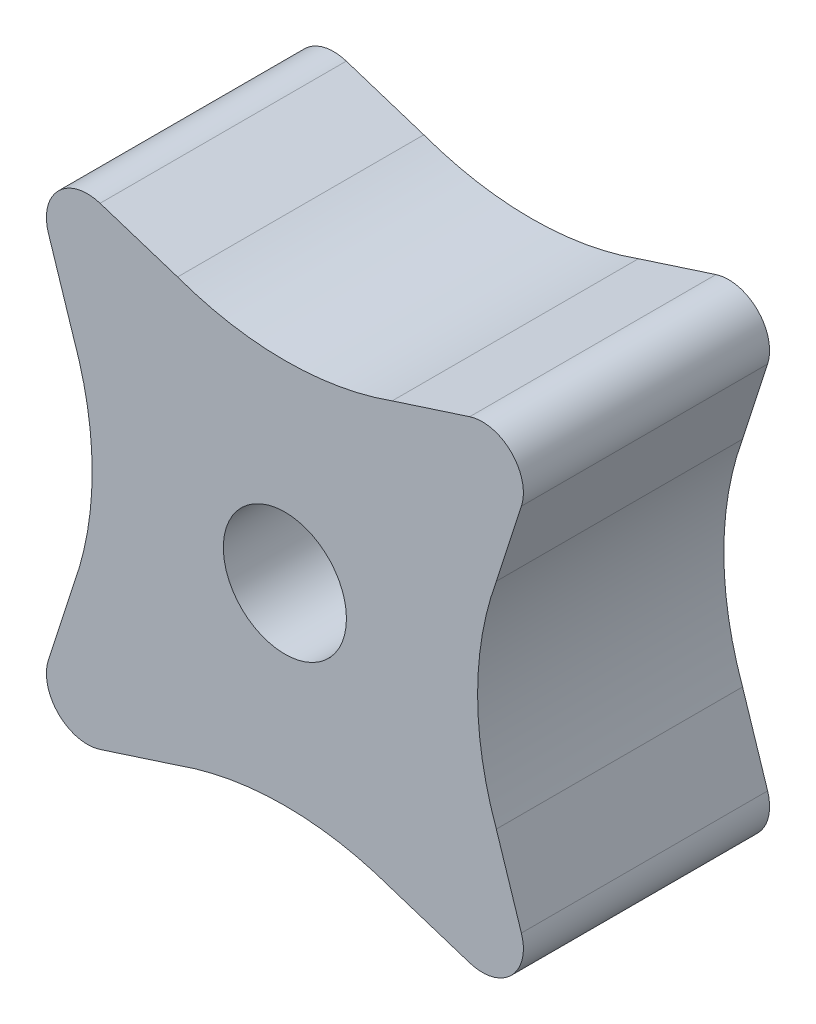
SolidWorks part; units mm, degrees
ref_plane "Alzado" through (0, 0, 0) normal (0, 0, 1) x (1, 0, 0)
ref_plane "Planta" through (0, 0, 0) normal (0, 1, 0) x (1, 0, 0)
ref_plane "Vista lateral" through (0, 0, 0) normal (1, 0, 0) x (0, 0, -1)
sketch "Croquis1" plane through (0, 0, 0) normal (0, 0, 1) x (1, 0, 0)
  line L0 (0, 0) -> (27.8544, 27.8544) construction
  line L1 (0, 0) -> (-42.4264, 42.4264) construction
  line L2 (0, 0) -> (0, 42.4264) construction
  line L3 (15.25, -15.25) -> (-15.25, -15.25) construction
  line L4 (15.25, -15.25) -> (15.25, 15.25) construction
  line L5 (15.25, 15.25) -> (-15.25, 15.25) construction
  line L6 (-15.25, -15.25) -> (-15.25, 15.25) construction
  line L7 (15.25, -15.25) -> (-15.25, 15.25) construction
  line L8 (15.25, 15.25) -> (-15.25, -15.25) construction
  line L9 (0, 42.4264) -> (-20, 42.4264) construction
  line L10 (-42.4264, 42.4264) -> (-38.8909, 45.9619) construction
  line L11 (-38.8909, 45.9619) -> (-31.0962, 38.1673) construction
  line L12 (-20, 42.7635) -> (-20, 80) construction
  line L13 (-42.4264, 42.4264) -> (-45.9619, 38.8909) construction
  line L14 (-45.9619, 38.8909) -> (-38.1673, 31.0962) construction
  line L15 (20, 42.7635) -> (20, 80) construction
  line L16 (38.8909, 45.9619) -> (31.0962, 38.1673) construction
  line L17 (42.4264, 42.4264) -> (38.8909, 45.9619) construction
  line L18 (42.4264, 42.4264) -> (45.9619, 38.8909) construction
  line L19 (-45.9619, -38.8909) -> (-38.1673, -31.0962) construction
  line L20 (0, 0) -> (-15.25, 0) construction
  line L21 (45.9619, 38.8909) -> (38.1673, 31.0962) construction
  line L22 (42.4264, -42.4264) -> (45.9619, -38.8909) construction
  line L23 (42.4264, -42.4264) -> (38.8909, -45.9619) construction
  line L24 (38.8909, -45.9619) -> (31.0962, -38.1673) construction
  line L25 (20, -42.7635) -> (20, -80) construction
  line L26 (-20, -42.7635) -> (-20, -80) construction
  line L27 (-38.8909, -45.9619) -> (-31.0962, -38.1673) construction
  line L28 (-42.4264, -42.4264) -> (-38.8909, -45.9619) construction
  line L29 (-42.4264, -42.4264) -> (-45.9619, -38.8909) construction
  line L30 (45.9619, -38.8909) -> (38.1673, -31.0962) construction
  line L31 (-20, 80) -> (20, 80) construction
  line L32 (0, 80) -> (0, 83) construction
  line L33 (-20, 80) -> (0, 83) construction
  line L34 (0, 83) -> (20, 80) construction
  line L35 (0, -80) -> (0, -83) construction
  line L36 (-20, -80) -> (20, -80) construction
  line L37 (0, -83) -> (20, -80) construction
  line L38 (-20, -80) -> (0, -83) construction
  line L39 (-11, -54) -> (-11, -67.5) construction
  line L41 (-15, -54) -> (-15, -67.5) construction
  line L43 (-13, -54) -> (-13, -67.5) construction
  line L44 (-9, -54) -> (-9, -67.5) construction
  line L45 (-7, -54) -> (-7, -67.5) construction
  line L46 (-5, -54) -> (-5, -67.5) construction
  line L47 (-3, -54) -> (-3, -67.5) construction
  line L48 (-1, -54) -> (-1, -67.5) construction
  line L49 (1, -54) -> (1, -67.5) construction
  line L50 (3, -54) -> (3, -67.5) construction
  line L51 (5, -54) -> (5, -67.5) construction
  line L52 (7, -54) -> (7, -67.5) construction
  line L53 (9, -54) -> (9, -67.5) construction
  line L54 (11, -54) -> (11, -67.5) construction
  line L55 (13, -54) -> (13, -67.5) construction
  line L56 (15, -54) -> (15, -67.5) construction
  line L57 (-11, -35) -> (-11, -48.5) construction
  line L58 (-9, -35) -> (-9, -48.5) construction
  line L59 (-7, -35) -> (-7, -48.5) construction
  line L60 (-5, -35) -> (-5, -48.5) construction
  line L61 (-3, -35) -> (-3, -48.5) construction
  line L62 (-1, -35) -> (-1, -48.5) construction
  line L63 (1, -35) -> (1, -48.5) construction
  line L64 (3, -35) -> (3, -48.5) construction
  line L65 (5, -35) -> (5, -48.5) construction
  line L66 (7, -35) -> (7, -48.5) construction
  line L67 (9, -35) -> (9, -48.5) construction
  line L68 (11, -35) -> (11, -48.5) construction
  line L69 (13, -35) -> (13, -48.5) construction
  line L70 (15, -35) -> (15, -48.5) construction
  line L71 (-15, -35) -> (-15, -48.5) construction
  line L72 (-13, -35) -> (-13, -48.5) construction
  line L73 (-15, 54) -> (-15, 67.5) construction
  line L74 (-13, 35) -> (-13, 48.5) construction
  line L75 (-15, 35) -> (-15, 48.5) construction
  line L76 (15, 35) -> (15, 48.5) construction
  line L77 (13, 35) -> (13, 48.5) construction
  line L78 (11, 35) -> (11, 48.5) construction
  line L79 (9, 35) -> (9, 48.5) construction
  line L80 (7, 35) -> (7, 48.5) construction
  line L81 (5, 35) -> (5, 48.5) construction
  line L82 (3, 35) -> (3, 48.5) construction
  line L83 (1, 35) -> (1, 48.5) construction
  line L84 (-1, 35) -> (-1, 48.5) construction
  line L85 (-3, 35) -> (-3, 48.5) construction
  line L86 (-5, 35) -> (-5, 48.5) construction
  line L87 (-7, 35) -> (-7, 48.5) construction
  line L88 (-9, 35) -> (-9, 48.5) construction
  line L89 (-11, 35) -> (-11, 48.5) construction
  line L90 (15, 54) -> (15, 67.5) construction
  line L91 (13, 54) -> (13, 67.5) construction
  line L92 (11, 54) -> (11, 67.5) construction
  line L93 (9, 54) -> (9, 67.5) construction
  line L94 (7, 54) -> (7, 67.5) construction
  line L95 (5, 54) -> (5, 67.5) construction
  line L96 (3, 54) -> (3, 67.5) construction
  line L97 (1, 54) -> (1, 67.5) construction
  line L98 (-1, 54) -> (-1, 67.5) construction
  line L99 (-3, 54) -> (-3, 67.5) construction
  line L100 (-5, 54) -> (-5, 67.5) construction
  line L101 (-7, 54) -> (-7, 67.5) construction
  line L102 (-9, 54) -> (-9, 67.5) construction
  line L103 (-13, 54) -> (-13, 67.5) construction
  line L104 (-11, 54) -> (-11, 67.5) construction
  line L105 (0, 0) -> (-8.4853, -8.4853) construction
  line L110 (-5.7118, -4.325) -> (-4.3076, -2.2188) construction
  line L111 (-4.325, -5.7118) -> (-2.2188, -4.3076) construction
  line L112 (-4.325, 5.7118) -> (-2.2188, 4.3076) construction
  line L113 (-5.7118, 4.325) -> (-4.3076, 2.2188) construction
  line L114 (5.7118, 4.325) -> (4.3076, 2.2188) construction
  line L115 (4.325, 5.7118) -> (2.2188, 4.3076) construction
  line L116 (4.325, -5.7118) -> (2.2188, -4.3076) construction
  line L117 (5.7118, -4.325) -> (4.3076, -2.2188) construction
  line L118 (0, 0) -> (-84.8528, 84.8528) construction
  line L123 (-45.9619, 38.8909) -> (-31.0962, 24.0251) construction
  line L124 (-17.1122, 2.2943) -> (-30.516, 23.1236) construction
  line L125 (-31.8543, 24.7832) -> (-45.9619, 38.8909) construction
  line L126 (-45.9619, 38.8909) -> (-74.3192, 67.2481) construction
  line L127 (-31.0962, 24.0251) -> (-24.0251, 31.0962) construction
  line L128 (-38.8909, 45.9619) -> (-24.0251, 31.0962) construction
  line L129 (-2.2943, 17.1122) -> (-23.1236, 30.516) construction
  line L130 (-24.7832, 31.8543) -> (-38.8909, 45.9619) construction
  line L131 (-84.8528, 84.8528) -> (-87.6812, 87.6812) construction
  line L132 (-84.8528, 84.8528) -> (-70.8528, 84.8528) construction
  line L133 (-83.3528, 77.8528) -> (-83.3528, 74.8528) construction
  line L134 (-86.3528, 77.8528) -> (-86.3528, 74.8528) construction
  line L135 (-84.8528, 84.8528) -> (-84.8528, 98.8528) construction
  line L136 (-77.8528, 84.8528) -> (-77.8528, 86.3528) construction
  line L137 (-77.8528, 86.3528) -> (-74.8528, 86.3528) construction
  line L138 (-77.8528, 84.8528) -> (-79.3528, 84.8528) construction
  line L139 (-74.8528, 86.3528) -> (-74.8528, 84.8528) construction
  line L140 (-74.8528, 84.8528) -> (-73.3528, 84.8528) construction
  line L141 (-77.8528, 83.3528) -> (-74.8528, 83.3528) construction
  line L148 (-87.6812, 87.6812) -> (-100.4092, 100.4092) construction
  line L149 (-84.8528, 70.8528) -> (-84.8528, 70.3528) construction
  line L150 (-98.8528, 84.8528) -> (-99.3528, 84.8528) construction
  line L151 (-84.8528, 70.3528) -> (-83.3528, 70.3528) construction
  line L152 (-84.8528, 70.3528) -> (-84.8669, 70.3528) construction
  line L153 (-99.3528, 84.8528) -> (-99.3528, 84.8388) construction
  line L154 (-84.8528, 98.8528) -> (-84.8528, 99.3528) construction
  line L155 (-99.3528, 84.8528) -> (-100.0987, 95.8369) construction
  line L157 (-95.9135, 92.7315) -> (-93.7922, 90.6102) construction
  line L159 (-90.6102, 93.7922) -> (-92.7315, 95.9135) construction
  line L160 (-95.8369, 100.0987) -> (-84.8528, 99.3528) construction
  line L161 (-91.8528, 83.3528) -> (-94.8528, 83.3528) construction
  line L162 (-91.8528, 86.3528) -> (-94.8528, 86.3528) construction
  line L163 (-86.3528, 91.8528) -> (-86.3528, 94.8528) construction
  line L164 (-83.3528, 91.8528) -> (-83.3528, 94.8528) construction
  line L165 (-84.8528, 84.8528) -> (-84.8528, 70.8528) construction
  line L166 (-70.3528, 84.8528) -> (-70.3528, 83.3528) construction
  line L167 (-84.8528, 84.8528) -> (-98.8528, 84.8528) construction
  line L168 (-38.8909, 45.9619) -> (-67.2481, 74.3192) construction
  line L169 (-70.3528, 84.8669) -> (-70.3528, 84.8528) construction
  line L170 (-84.8528, 99.3528) -> (-84.8388, 99.3528) construction
  line L171 (0, 0) -> (-6.364, 6.364) construction
  line L172 (-5.7629, 4.5039) -> (-5.1526, 2.6149) construction
  line L173 (-7.0557, 0) -> (-12.9076, 0) construction
  line L174 (-4.5039, 5.7629) -> (-2.6149, 5.1526) construction
  line L175 (0, 7.0557) -> (0, 12.9076) construction
  line L176 (-5.1526, 2.6149) -> (-5.7629, 4.5039)
  line L177 (-4.5039, 5.7629) -> (-2.6149, 5.1526)
  line L178 (2.6149, 5.1526) -> (4.5039, 5.7629)
  line L179 (5.7629, 4.5039) -> (5.1526, 2.6149)
  line L180 (5.1526, -2.6149) -> (5.7629, -4.5039)
  line L181 (4.5039, -5.7629) -> (2.6149, -5.1526)
  line L182 (-2.6149, -5.1526) -> (-4.5039, -5.7629)
  line L183 (-5.7629, -4.5039) -> (-5.1526, -2.6149)
  circle A0 centre (-15.25, 15.25) radius 4 construction
  circle A1 centre (-24.0416, 24.0416) radius 1.5 construction
  circle A2 centre (-38.8909, 38.8909) radius 1.5 construction
  arc A3 (-31.0962, 38.1673) -> (-20, 42.7635) centre (-26.5, 42.7635) ccw construction
  arc A4 (31.0962, 38.1673) -> (20, 42.7635) centre (26.5, 42.7635) cw construction
  circle A5 centre (38.8909, 38.8909) radius 1.5 construction
  circle A6 centre (24.0416, 24.0416) radius 1.5 construction
  circle A7 centre (15.25, 15.25) radius 4 construction
  circle A8 centre (15.25, -15.25) radius 4 construction
  circle A9 centre (24.0416, -24.0416) radius 1.5 construction
  circle A10 centre (38.8909, -38.8909) radius 1.5 construction
  arc A11 (31.0962, -38.1673) -> (20, -42.7635) centre (26.5, -42.7635) ccw construction
  circle A12 centre (-15.25, -15.25) radius 4 construction
  circle A13 centre (-24.0416, -24.0416) radius 1.5 construction
  circle A14 centre (-38.8909, -38.8909) radius 1.5 construction
  arc A15 (-31.0962, -38.1673) -> (-20, -42.7635) centre (-26.5, -42.7635) cw construction
  arc A16 (-38.1673, -31.0962) -> (-38.1673, 31.0962) centre (-69.2635, 0) ccw construction
  arc A17 (38.1673, -31.0962) -> (38.1673, 31.0962) centre (69.2635, 0) cw construction
  circle A18 centre (0, 0) radius 1.5 construction
  circle A19 centre (-16, -75) radius 1.5 construction
  circle A20 centre (-16, -30) radius 1.5 construction
  circle A21 centre (-16, 30) radius 1.5 construction
  circle A22 centre (-16, 75) radius 1.5 construction
  circle A23 centre (16, -75) radius 1.5 construction
  circle A24 centre (16, -30) radius 1.5 construction
  circle A25 centre (16, 30) radius 1.5 construction
  circle A26 centre (16, 75) radius 1.5 construction
  arc A27 (-15, -54) -> (-13, -54) centre (-14, -54) cw construction
  arc A28 (-15, -67.5) -> (-13, -67.5) centre (-14, -67.5) ccw construction
  arc A29 (-11, -54) -> (-9, -54) centre (-10, -54) cw construction
  arc A30 (-11, -67.5) -> (-9, -67.5) centre (-10, -67.5) ccw construction
  arc A31 (-7, -54) -> (-5, -54) centre (-6, -54) cw construction
  arc A32 (-7, -67.5) -> (-5, -67.5) centre (-6, -67.5) ccw construction
  arc A33 (-3, -54) -> (-1, -54) centre (-2, -54) cw construction
  arc A34 (-3, -67.5) -> (-1, -67.5) centre (-2, -67.5) ccw construction
  arc A35 (1, -54) -> (3, -54) centre (2, -54) cw construction
  arc A36 (1, -67.5) -> (3, -67.5) centre (2, -67.5) ccw construction
  arc A37 (5, -54) -> (7, -54) centre (6, -54) cw construction
  arc A38 (5, -67.5) -> (7, -67.5) centre (6, -67.5) ccw construction
  arc A39 (9, -54) -> (11, -54) centre (10, -54) cw construction
  arc A40 (9, -67.5) -> (11, -67.5) centre (10, -67.5) ccw construction
  arc A41 (13, -54) -> (15, -54) centre (14, -54) cw construction
  arc A42 (13, -67.5) -> (15, -67.5) centre (14, -67.5) ccw construction
  arc A43 (-11, -35) -> (-9, -35) centre (-10, -35) cw construction
  arc A44 (-11, -48.5) -> (-9, -48.5) centre (-10, -48.5) ccw construction
  arc A45 (-7, -35) -> (-5, -35) centre (-6, -35) cw construction
  arc A46 (-7, -48.5) -> (-5, -48.5) centre (-6, -48.5) ccw construction
  arc A47 (-3, -35) -> (-1, -35) centre (-2, -35) cw construction
  arc A48 (-3, -48.5) -> (-1, -48.5) centre (-2, -48.5) ccw construction
  arc A49 (1, -35) -> (3, -35) centre (2, -35) cw construction
  arc A50 (1, -48.5) -> (3, -48.5) centre (2, -48.5) ccw construction
  arc A51 (5, -35) -> (7, -35) centre (6, -35) cw construction
  arc A52 (5, -48.5) -> (7, -48.5) centre (6, -48.5) ccw construction
  arc A53 (9, -35) -> (11, -35) centre (10, -35) cw construction
  arc A54 (9, -48.5) -> (11, -48.5) centre (10, -48.5) ccw construction
  arc A55 (13, -35) -> (15, -35) centre (14, -35) cw construction
  arc A56 (13, -48.5) -> (15, -48.5) centre (14, -48.5) ccw construction
  arc A57 (-15, -35) -> (-13, -35) centre (-14, -35) cw construction
  arc A58 (-15, -48.5) -> (-13, -48.5) centre (-14, -48.5) ccw construction
  arc A59 (-15, 48.5) -> (-13, 48.5) centre (-14, 48.5) cw construction
  arc A60 (-15, 35) -> (-13, 35) centre (-14, 35) ccw construction
  arc A61 (13, 48.5) -> (15, 48.5) centre (14, 48.5) cw construction
  arc A62 (13, 35) -> (15, 35) centre (14, 35) ccw construction
  arc A63 (9, 48.5) -> (11, 48.5) centre (10, 48.5) cw construction
  arc A64 (9, 35) -> (11, 35) centre (10, 35) ccw construction
  arc A65 (5, 48.5) -> (7, 48.5) centre (6, 48.5) cw construction
  arc A66 (5, 35) -> (7, 35) centre (6, 35) ccw construction
  arc A67 (1, 48.5) -> (3, 48.5) centre (2, 48.5) cw construction
  arc A68 (1, 35) -> (3, 35) centre (2, 35) ccw construction
  arc A69 (-3, 48.5) -> (-1, 48.5) centre (-2, 48.5) cw construction
  arc A70 (-3, 35) -> (-1, 35) centre (-2, 35) ccw construction
  arc A71 (-7, 48.5) -> (-5, 48.5) centre (-6, 48.5) cw construction
  arc A72 (-7, 35) -> (-5, 35) centre (-6, 35) ccw construction
  arc A73 (-11, 48.5) -> (-9, 48.5) centre (-10, 48.5) cw construction
  arc A74 (-11, 35) -> (-9, 35) centre (-10, 35) ccw construction
  arc A75 (13, 67.5) -> (15, 67.5) centre (14, 67.5) cw construction
  arc A76 (13, 54) -> (15, 54) centre (14, 54) ccw construction
  arc A77 (9, 67.5) -> (11, 67.5) centre (10, 67.5) cw construction
  arc A78 (9, 54) -> (11, 54) centre (10, 54) ccw construction
  arc A79 (5, 67.5) -> (7, 67.5) centre (6, 67.5) cw construction
  arc A80 (5, 54) -> (7, 54) centre (6, 54) ccw construction
  arc A81 (1, 67.5) -> (3, 67.5) centre (2, 67.5) cw construction
  arc A82 (1, 54) -> (3, 54) centre (2, 54) ccw construction
  arc A83 (-3, 67.5) -> (-1, 67.5) centre (-2, 67.5) cw construction
  arc A84 (-3, 54) -> (-1, 54) centre (-2, 54) ccw construction
  arc A85 (-7, 67.5) -> (-5, 67.5) centre (-6, 67.5) cw construction
  arc A86 (-7, 54) -> (-5, 54) centre (-6, 54) ccw construction
  arc A87 (-11, 67.5) -> (-9, 67.5) centre (-10, 67.5) cw construction
  arc A88 (-11, 54) -> (-9, 54) centre (-10, 54) ccw construction
  arc A89 (-15, 67.5) -> (-13, 67.5) centre (-14, 67.5) cw construction
  arc A90 (-15, 54) -> (-13, 54) centre (-14, 54) ccw construction
  arc A91 (-4.325, -5.7118) -> (-5.7118, -4.325) centre (-4.8797, -4.8797) cw construction
  arc A92 (-5.7118, 4.325) -> (-4.325, 5.7118) centre (-4.8797, 4.8797) cw construction
  arc A93 (4.325, 5.7118) -> (5.7118, 4.325) centre (4.8797, 4.8797) cw construction
  arc A94 (5.7118, -4.325) -> (4.325, -5.7118) centre (4.8797, -4.8797) cw construction
  circle A95 centre (0, 0) radius 1.5 construction
  arc A96 (2.2188, -4.3076) -> (-2.2188, -4.3076) centre (0, -7.6358) ccw construction
  arc A97 (4.3076, 2.2188) -> (4.3076, -2.2188) centre (7.6358, 0) ccw construction
  arc A98 (-2.2188, 4.3076) -> (2.2188, 4.3076) centre (0, 7.6358) ccw construction
  arc A99 (-4.3076, 2.2188) -> (-4.3076, -2.2188) centre (-7.6358, 0) cw construction
  circle A100 centre (-84.8528, 84.8528) radius 65 construction
  circle A101 centre (-84.8528, 84.8528) radius 4 construction
  circle A102 centre (-38.8909, 38.8909) radius 1.5 construction
  circle A103 centre (-24.0416, 24.0416) radius 1.5 construction
  circle A104 centre (-15.25, 15.25) radius 4 construction
  arc A112 (0, 12.9076) -> (-2.2943, 17.1122) centre (-5, 12.9076) ccw construction
  arc A113 (-12.9076, 0) -> (-17.1122, 2.2943) centre (-12.9076, 5) cw construction
  arc A114 (-23.1236, 30.516) -> (-24.7832, 31.8543) centre (-17.7121, 38.9253) cw construction
  arc A115 (-31.8543, 24.7832) -> (-30.516, 23.1236) centre (-38.9253, 17.7121) cw construction
  arc A116 (-77.8528, 83.3528) -> (-77.8528, 86.3528) centre (-77.8528, 84.8528) cw construction
  arc A117 (-74.8528, 86.3528) -> (-74.8528, 83.3528) centre (-74.8528, 84.8528) cw construction
  arc A124 (-80.0325, 70.0845) -> (-83.3528, 70.3528) centre (-84.1058, 40.3623) ccw construction
  arc A125 (-87.0345, 71.6072) -> (-98.0984, 82.6712) centre (-113.0456, 56.66) ccw construction
  arc A126 (-84.8669, 70.3528) -> (-87.0345, 71.6072) centre (-84.8669, 72.8528) cw construction
  arc A127 (-99.3528, 84.8388) -> (-98.0984, 82.6712) centre (-96.8528, 84.8388) ccw construction
  arc A128 (-100.0987, 95.8369) -> (-95.8369, 100.0987) centre (-96.1079, 96.1079) cw construction
  arc A129 (-95.9135, 92.7315) -> (-92.7315, 95.9135) centre (-94.3225, 94.3225) cw construction
  arc A130 (-93.7922, 90.6102) -> (-90.6102, 93.7922) centre (-92.2012, 92.2012) ccw construction
  arc A131 (-74.3192, 67.2481) -> (-80.0325, 70.0845) centre (-81.3903, 60.1771) ccw construction
  arc A132 (-86.3528, 77.8528) -> (-83.3528, 77.8528) centre (-84.8528, 77.8528) cw construction
  arc A133 (-83.3528, 74.8528) -> (-86.3528, 74.8528) centre (-84.8528, 74.8528) cw construction
  arc A134 (-91.8528, 86.3528) -> (-91.8528, 83.3528) centre (-91.8528, 84.8528) cw construction
  arc A135 (-94.8528, 83.3528) -> (-94.8528, 86.3528) centre (-94.8528, 84.8528) cw construction
  arc A136 (-83.3528, 91.8528) -> (-86.3528, 91.8528) centre (-84.8528, 91.8528) cw construction
  arc A137 (-86.3528, 94.8528) -> (-83.3528, 94.8528) centre (-84.8528, 94.8528) cw construction
  arc A138 (-84.8388, 99.3528) -> (-82.6712, 98.0984) centre (-84.8388, 96.8528) cw construction
  arc A139 (-71.6072, 87.0345) -> (-82.6712, 98.0984) centre (-56.66, 113.0456) cw construction
  arc A140 (-70.3528, 84.8669) -> (-71.6072, 87.0345) centre (-72.8528, 84.8669) ccw construction
  arc A141 (-70.0845, 80.0325) -> (-70.3528, 83.3528) centre (-40.3623, 84.1058) cw construction
  arc A142 (-67.2481, 74.3192) -> (-70.0845, 80.0325) centre (-60.1771, 81.3903) cw construction
  arc A143 (-4.5039, 5.7629) -> (-5.7629, 4.5039) centre (-4.8114, 4.8114) ccw construction
  arc A144 (-2.6149, 5.1526) -> (0, 7.0557) centre (-2, 7.0557) ccw construction
  arc A145 (-5.1526, 2.6149) -> (-7.0557, 0) centre (-7.0557, 2) cw construction
  arc A146 (-5.7629, 4.5039) -> (-4.5039, 5.7629) centre (-4.8114, 4.8114) cw
  arc A147 (4.5039, 5.7629) -> (5.7629, 4.5039) centre (4.8114, 4.8114) cw
  arc A148 (5.7629, -4.5039) -> (4.5039, -5.7629) centre (4.8114, -4.8114) cw
  arc A149 (-4.5039, -5.7629) -> (-5.7629, -4.5039) centre (-4.8114, -4.8114) cw
  arc A150 (-2.6149, 5.1526) -> (2.6149, 5.1526) centre (0, 12.4149) ccw
  arc A151 (5.1526, 2.6149) -> (5.1526, -2.6149) centre (12.4149, 0) ccw
  arc A152 (2.6149, -5.1526) -> (-2.6149, -5.1526) centre (0, -12.4149) ccw
  arc A153 (-5.1526, -2.6149) -> (-5.1526, 2.6149) centre (-12.4149, 0) ccw
  circle A154 centre (0, 0) radius 1.5
  point P35 (-34.9935, 42.0646)
  point P37 (44.1942, 40.6586)
  point P45 (44.1942, -40.6586)
  point P61 (-34.9935, -42.0646)
  point P305 (0, 0)
  point P308 (-2.8284, 0)
  point P327 (0, 4.3076)
  point P330 (-4.3076, 0)
  point P338 (0, 15.6358)
  point P341 (-15.6358, 0)
  point P354 (-84.8528, 84.8528)
  point P383 (-85.9522, 83.739)
  point P393 (-86.3528, 70.3528)
  point P396 (-99.3528, 83.3528)
  point P411 (-84.8528, 84.8528)
  point P440 (0, 0)
  point P451 (0, 0)
  dimension "D2" = 8
  dimension "D4" = 5
  dimension "D8" = 6.5
  dimension "D10" = 3
  dimension "D11" = 3
  dimension "D13" = 4
  dimension "D15" = 3
  dimension "D16" = 3
  dimension "D18" = 45
  dimension "D26" = 1
  dimension "D28" = 4
  dimension "D29" = 130
  dimension "D31" = 4
  dimension "D32" = 9
  dimension "D33" = 5
  dimension "D34" = 10
  dimension "D43" = 1.5
  dimension "D45" = 30
  dimension "D46" = 30
  dimension "D49" = 4
  dimension "D50" = 2.5
  dimension "D48" = 0.5
  dimension "D55" = 10
  dimension "D51" = 4
  dimension "D39" = 1
  dimension "D40" = 2
  dimension "D1" = 30.5
  dimension "D3" = 60
  dimension "D5" = 21
  dimension "D6" = 20
  dimension "D7" = 5
  dimension "D9" = 5
  dimension "D12" = 80
  dimension "D14" = 5
  dimension "D17" = 4
  dimension "D19" = 2
  dimension "D20" = 13.5
  dimension "D21" = 7.5
  dimension "D22" = 5
  dimension "D25" = 12
  dimension "D30" = 120
  dimension "D35" = 14
  dimension "D37" = 3
  dimension "D38" = 1.5
  dimension "D41" = 4
  dimension "D42" = 0.5
  dimension "D44" = 1.5
  dimension "D47" = 1.5
  dimension "D52" = 2.25
  dimension "D53" = 2.25
  dimension "D54" = 3
  dimension "D23" = 8
  dimension "D24" = 2
  dimension "D27" = 4
  dimension "D36" = 4
extrude "Saliente-Extruir1" add sketch "Croquis1" along normal blind 6
